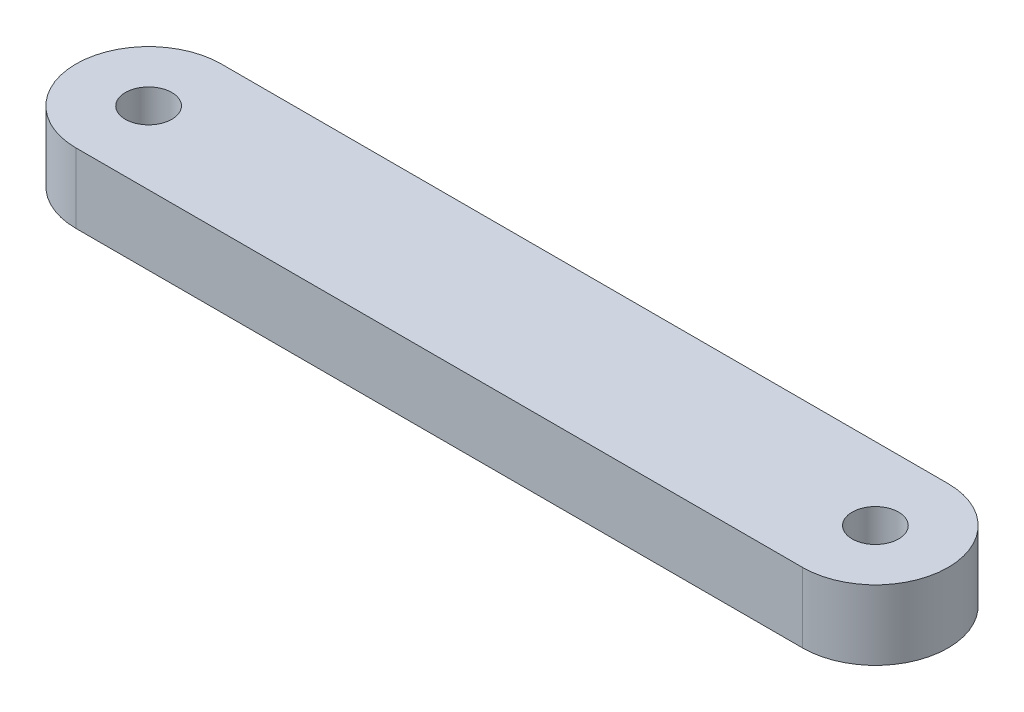
SolidWorks part; units mm, degrees
ref_plane "正面" through (0, 0, 0) normal (0, 0, 1) x (1, 0, 0)
ref_plane "平面" through (0, 0, 0) normal (0, 1, 0) x (1, 0, 0)
ref_plane "右側面" through (0, 0, 0) normal (1, 0, 0) x (0, 0, -1)
sketch "ｽｹｯﾁ1" plane through (0, 0, 0) normal (0, 1, 0) x (1, 0, 0)
  line L0 (-25, 0) -> (25, 0) construction
  line L1 (-25, 5) -> (25, 5)
  line L2 (-25, -5) -> (25, -5)
  arc A0 (-25, 5) -> (-25, -5) centre (-25, 0) ccw
  arc A1 (25, -5) -> (25, 5) centre (25, 0) ccw
  circle A2 centre (-25, 0) radius 1.6
  circle A3 centre (25, 0) radius 1.6
  point P3 (0, 0)
  dimension "D1" = 3.2
  dimension "D3" = 5
  dimension "D2" = 50
extrude "ﾎﾞｽ - 押し出し1" add sketch "ｽｹｯﾁ1" along normal blind 4.8
